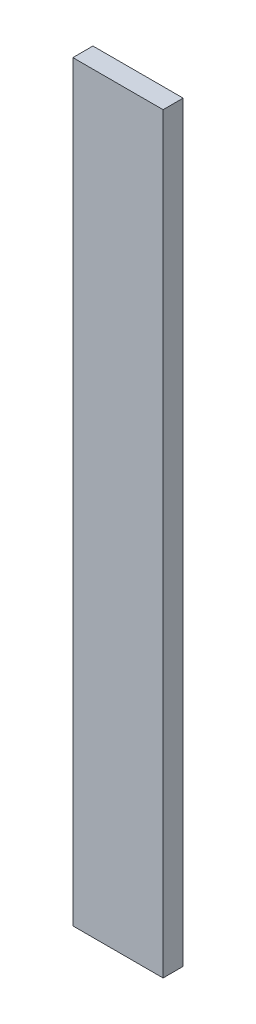
SolidWorks part; units mm, degrees
ref_plane "Front Plane" through (0, 0, 0) normal (0, 0, 1) x (1, 0, 0)
ref_plane "Top Plane" through (0, 0, 0) normal (0, 1, 0) x (1, 0, 0)
ref_plane "Right Plane" through (0, 0, 0) normal (1, 0, 0) x (0, 0, -1)
sketch "Sketch1" plane through (0, 0, 0) normal (0, 0, 1) x (1, 0, 0)
  line L1 (0, 0) -> (450, 0)
  line L2 (0, 0) -> (0, -3750)
  line L3 (0, -3750) -> (450, -3750)
  line L4 (450, 0) -> (450, -3750)
  dimension "D1" = 3750
  dimension "D2" = 450
extrude "Boss-Extrude1" add sketch "Sketch1" along normal blind 100
